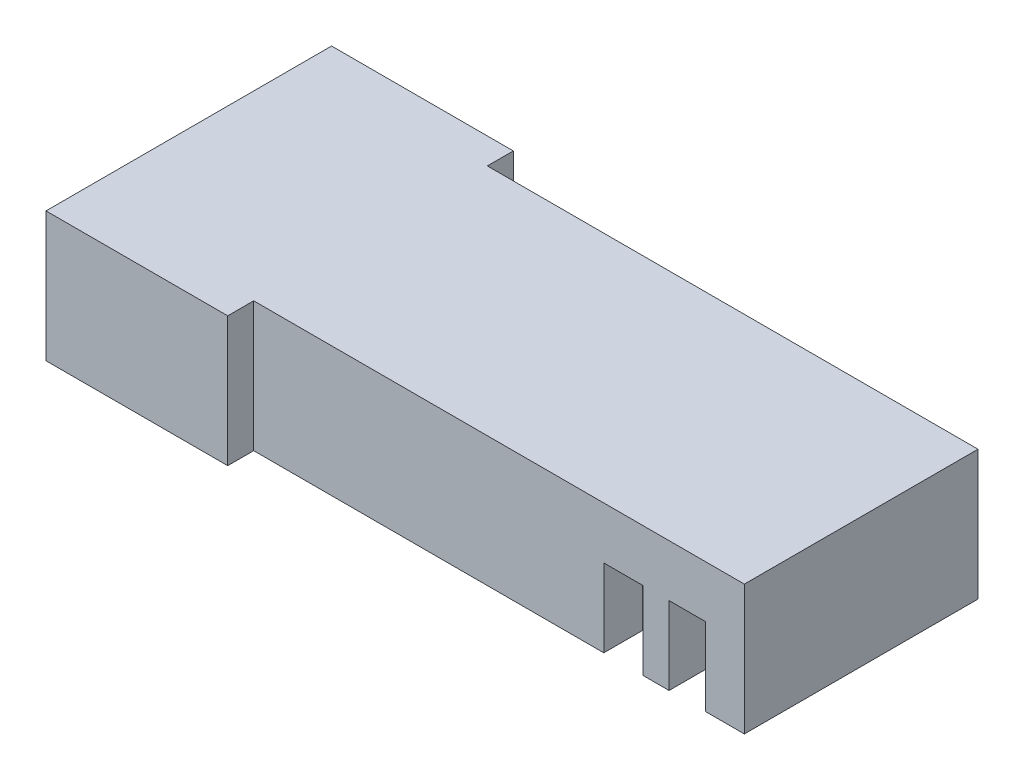
SolidWorks part; units mm, degrees
ref_plane "Front Plane" through (0, 0, 0) normal (0, 0, 1) x (1, 0, 0)
ref_plane "Top Plane" through (0, 0, 0) normal (0, 1, 0) x (1, 0, 0)
ref_plane "Right Plane" through (0, 0, 0) normal (1, 0, 0) x (0, 0, -1)
sketch "Sketch1" plane through (0, 0, 0) normal (0, 1, 0) x (1, 0, 0)
  line L1 (-7.5, -4.5) -> (7.5, -4.5)
  line L3 (-7.5, 4.5) -> (7.5, 4.5)
  line L5 (-7.5, -4.5) -> (7.5, 4.5) construction
  line L6 (-7.5, 4.5) -> (7.5, -4.5) construction
  line L10 (-7.5, 4.5) -> (-7.5, 5.5)
  line L11 (-7.5, 5.5) -> (-14.5, 5.5)
  line L12 (-14.5, 5.5) -> (-14.5, -5.5)
  line L13 (-14.5, -5.5) -> (-7.5, -5.5)
  line L14 (-7.5, -5.5) -> (-7.5, -4.5)
  line L16 (7.5, 4.5) -> (11.4, 4.5)
  line L17 (11.4, 4.5) -> (11.4, -4.5)
  line L18 (11.4, -4.5) -> (7.5, -4.5)
  point P0 (0, 0)
  dimension "D1" = 9
  dimension "D2" = 15
  dimension "D3" = 3.9
  dimension "D6" = 1
  dimension "D7" = 7
extrude "Boss-Extrude1" add sketch "Sketch1" along normal blind 2
sketch "Sketch2" plane through (0, 0, 0) normal (0, 1, 0) x (1, 0, 0)
  line L0 (7.5, 4.5) -> (-7.5, 4.5)
  line L1 (-7.5, 4.5) -> (-7.5, 5.5)
  line L2 (-7.5, 5.5) -> (-14.5, 5.5)
  line L3 (-14.5, 5.5) -> (-14.5, 3.5)
  line L4 (-14.5, 5.5) -> (-14.5, -5.5) construction
  line L5 (-14.5, 3.5) -> (0.5, 3.5)
  line L6 (0.5, 3.5) -> (0.5, 3)
  line L7 (0.5, 3) -> (7.5, 3)
  line L12 (-7.5, -4.5) -> (-7.5, -5.5)
  line L13 (-7.5, -5.5) -> (-14.5, -5.5)
  line L14 (-14.5, -5.5) -> (-14.5, -3.5)
  line L15 (-14.5, -3.5) -> (0.5, -3.5)
  line L16 (0.5, -3.5) -> (0.5, -3)
  line L20 (0.5, 1.6) -> (7.5, 1.6)
  line L22 (7.5, -1.6) -> (0.5, -1.6)
  line L23 (0.5, -1.6) -> (0.5, 1.6)
  line L24 (-7.5, -4.5) -> (5.9862, -4.5)
  line L25 (-7.5, -4.5) -> (11.4, -4.5) construction
  line L26 (5.9862, -4.5) -> (5.9862, -3)
  line L27 (5.9862, -3) -> (0.5, -3)
  line L28 (7.5, 3) -> (9.9, 3)
  line L29 (9.9, 3) -> (9.9, -4.5)
  line L30 (9.9, -4.5) -> (11.4, -4.5)
  line L31 (11.4, -4.5) -> (11.4, 4.5)
  line L32 (11.4, 4.5) -> (7.5, 4.5)
  line L33 (7.5, 1.6) -> (8.5, 1.6)
  line L34 (8.5, 1.6) -> (8.5, -4.5)
  line L35 (8.5, -4.5) -> (7.5, -4.5)
  line L36 (7.5, -4.5) -> (7.5, -1.6)
  dimension "D1" = 1.5
  dimension "D2" = 7
  dimension "D3" = 2.4
  dimension "D4" = 1.4
  dimension "D5" = 2
  dimension "D6" = 1.5
  dimension "D7" = 1
extrude "Boss-Extrude2" add sketch "Sketch2" against normal blind 3
sketch "Sketch3" plane through (0, -3, 0) normal (0, -1, 0) x (1, 0, 0)
  line L0 (-14.5, 5.5) -> (-14.5, 2.3911)
  line L1 (-14.5, -3.5) -> (-14.5, 3.5) construction
  line L2 (-7.5, 5.5) -> (-14.5, 5.5)
  line L3 (-7.5, 5.5) -> (-7.5, 2.3911)
  line L4 (-7.5, 2.3911) -> (-14.5, 2.3911)
  line L5 (-7.5, -5.5) -> (-14.5, -5.5)
  line L6 (-14.5, -5.5) -> (-14.5, -2.3911)
  line L7 (-7.5, -5.5) -> (-7.5, -2.3911)
  line L8 (-7.5, -2.3911) -> (-14.5, -2.3911)
  dimension "D1" = 3.1089
extrude "Boss-Extrude3" add sketch "Sketch3" against normal blind 2
